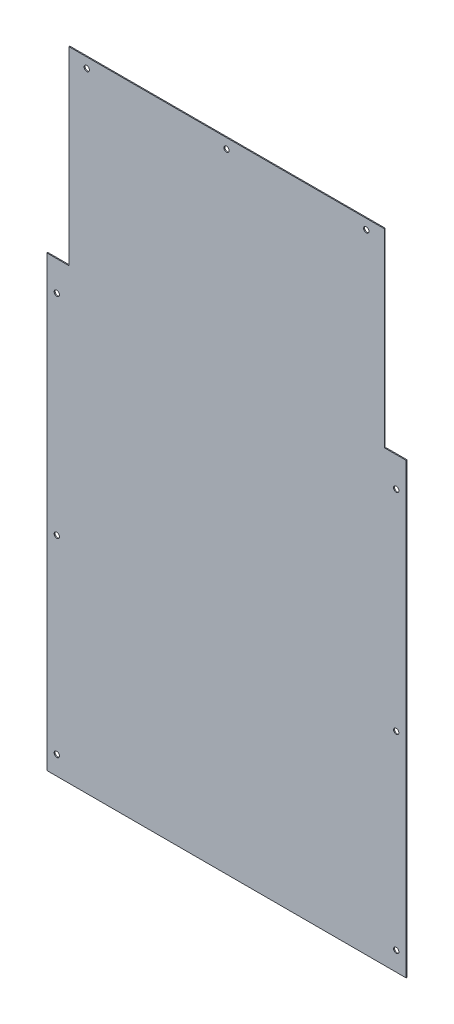
SolidWorks part; units mm, degrees
material "1023 Carbon Steel Sheet (SS)"
ref_plane "Front Plane" through (0, 0, 0) normal (0, 0, 1) x (1, 0, 0)
ref_plane "Top Plane" through (0, 0, 0) normal (0, 1, 0) x (1, 0, 0)
ref_plane "Right Plane" through (0, 0, 0) normal (1, 0, 0) x (0, 0, -1)
sketch "Sketch1" plane through (0, 0, 0) normal (0, 0, 1) x (1, 0, 0)
  line L1 (0, 0) -> (457.2, 0)
  line L2 (0, 0) -> (0, 840.74)
  line L3 (0, 840.74) -> (457.2, 840.74)
  line L4 (457.2, 0) -> (457.2, 840.74)
  line L5 (12.7, 815.34) -> (444.5, 815.34) construction
  line L6 (12.7, 815.34) -> (12.7, 25.4) construction
  line L7 (12.7, 25.4) -> (444.5, 25.4) construction
  line L8 (444.5, 815.34) -> (444.5, 25.4) construction
  dimension "D1" = 840.74
  dimension "D2" = 457.2
  dimension "D3" = 12.7
  dimension "D4" = 12.7
  dimension "D5" = 25.4
  dimension "D6" = 25.4
extrude "Boss-Extrude1" add sketch "Sketch1" along normal blind 1.2192
sketch "Sketch5" plane through (0, 0, 1.2192) normal (0, 0, 1) x (1, 0, 0)
  line L0 (457.2, 840.74) -> (0, 840.74) construction
  line L1 (0, 840.74) -> (457.2, 840.74)
  line L2 (0, 840.74) -> (0, 811.53)
  line L3 (0, 811.53) -> (457.2, 811.53)
  line L4 (457.2, 840.74) -> (457.2, 811.53)
  line L5 (0, 840.74) -> (0, 0) construction
  line L6 (457.2, 0) -> (457.2, 840.74) construction
  line L8 (0, 811.53) -> (27.94, 811.53)
  line L9 (0, 811.53) -> (0, 570.23)
  line L10 (0, 570.23) -> (27.94, 570.23)
  line L11 (27.94, 811.53) -> (27.94, 570.23)
  line L12 (457.2, 811.53) -> (429.26, 811.53)
  line L13 (457.2, 811.53) -> (457.2, 570.23)
  line L14 (457.2, 570.23) -> (429.26, 570.23)
  line L15 (429.26, 811.53) -> (429.26, 570.23)
  line M1 (0, 840.74) -> (0, 0)
  line M3 (457.2, 0) -> (457.2, 840.74)
  line M4 (457.2, 840.74) -> (0, 840.74)
  dimension "D1" = 29.21
  dimension "D2" = 27.94
  dimension "D3" = 27.94
  dimension "D4" = 241.3
  dimension "D5" = 241.3
extrude "Cut-Extrude1" cut sketch "Sketch5" against normal blind 1.2192 contours L11 L3 L10 M1 | L3 M1 M3 M4 | L13 L14 L15 L12
sketch "Sketch6" plane through (0, 0, 1.2192) normal (0, 0, 1) x (1, 0, 0)
  line L0 (27.94, 811.53) -> (429.26, 811.53) construction
  line L1 (12.7, 798.83) -> (444.5, 798.83) construction
  line L2 (12.7, 798.83) -> (12.7, 24.13) construction
  line L3 (12.7, 24.13) -> (444.5, 24.13) construction
  line L4 (444.5, 798.83) -> (444.5, 24.13) construction
  line L5 (0, 570.23) -> (0, 0) construction
  line L6 (457.2, 0) -> (457.2, 570.23) construction
  point P12 (50.8, 798.83)
  point P13 (228.6, 798.83)
  point P14 (406.4, 798.83)
  point P15 (12.7, 532.13)
  point P16 (12.7, 265.43)
  point P17 (444.5, 265.43)
  point P18 (12.7, 24.13)
  point P19 (444.5, 24.13)
  point P20 (444.5, 532.13)
  dimension "D1" = 12.7
  dimension "D2" = 12.7
  dimension "D3" = 12.7
  dimension "D4" = 241.3
  dimension "D5" = 266.7
  dimension "D6" = 266.7
  dimension "D7" = 266.7
  dimension "D8" = 266.7
  dimension "D9" = 38.1
  dimension "D10" = 38.1
hole_wizard "1/4 Clearance Hole2" positions "Sketch8" profile "Sketch7" hole size "1/4" standard "ANSI Inch" end condition through all
sketch "Sketch8" plane through (0, 0, 1.2192) normal (0, 0, 1) x (1, 0, 0)
  point P0 (50.8, 798.83)
  point P3 (228.6, 798.83)
  point P6 (406.4, 798.83)
  point P9 (12.7, 532.13)
  point P12 (12.7, 265.43)
  point P15 (12.7, 24.13)
  point P18 (444.5, 24.13)
  point P21 (444.5, 265.43)
  point P24 (444.5, 532.13)
sketch "Sketch7" plane through (50.8, 798.83, 1.2192) normal (1, 0, 0) x (0, -1, 0)
  line L0 (0, 0) -> (0, 1.2192)
  line L1 (0, 1.2192) -> (3.3782, 1.2192)
  line L2 (3.3782, 1.2192) -> (3.3782, 0)
  line L5 (3.3782, 0) -> (0, 0)
  line L11 (0, -6.35) -> (0, 107.95) construction
  dimension "Thru Hole Dia." = 6.7564
  dimension "Thru Hole Depth" = 1.2192
equation "\"d1\"=0.5"
equation "\"D3@Sketch1\"=\"d1\""
equation "\"D4@Sketch1\"=\"d1\""
equation "\"d2\"=1"
equation "\"D3@Sketch6\"=\"d1\""
equation "\"D2@Sketch6\"=\"d1\""
equation "\"d3\"=10.5"
equation "\"D8@Sketch6\"=\"d3\""
equation "\"D6@Sketch6\"=\"d3\""
equation "\"D5@Sketch6\"=\"d3\""
equation "\"D7@Sketch6\"=\"d3\""
